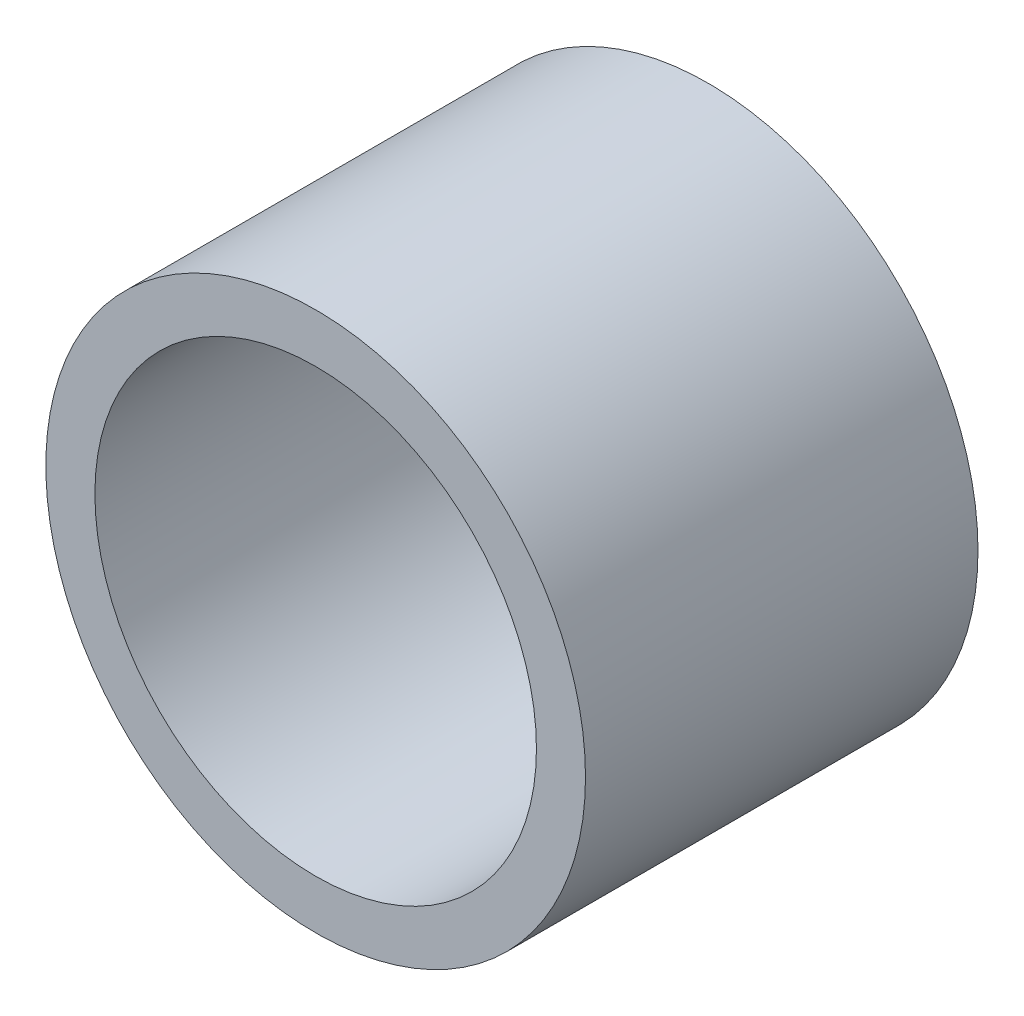
SolidWorks part; units mm, degrees
ref_plane "前视基准面" through (0, 0, 0) normal (0, 0, 1) x (1, 0, 0)
ref_plane "上视基准面" through (0, 0, 0) normal (0, 1, 0) x (1, 0, 0)
ref_plane "右视基准面" through (0, 0, 0) normal (1, 0, 0) x (0, 0, -1)
sketch "草图1" plane through (0, 0, 0) normal (0, 0, 1) x (1, 0, 0)
  circle A0 centre (0, 0) radius 4.5
  circle A1 centre (0, 0) radius 5.5
  dimension "D1" = 9
  dimension "D2" = 11
extrude "凸台-拉伸1" add sketch "草图1" along normal blind 8
